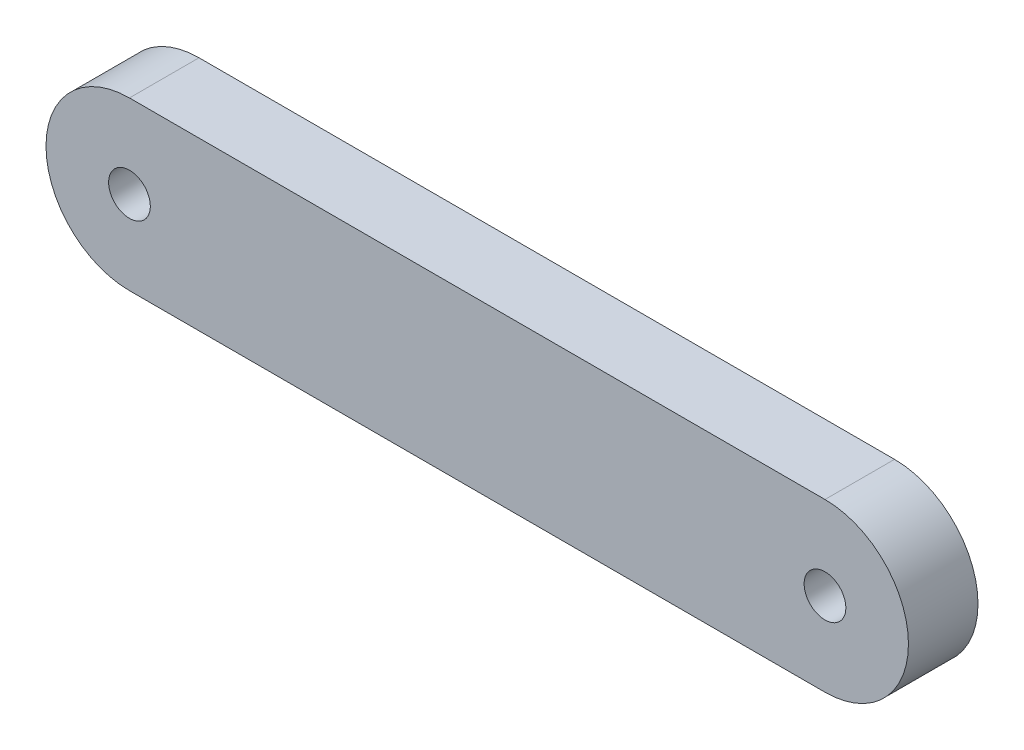
SolidWorks part; units mm, degrees
ref_plane "Plan de face" through (0, 0, 0) normal (0, 0, 1) x (1, 0, 0)
ref_plane "Plan de dessus" through (0, 0, 0) normal (0, 1, 0) x (1, 0, 0)
ref_plane "Plan de droite" through (0, 0, 0) normal (1, 0, 0) x (0, 0, -1)
sketch "Esquisse1" plane through (0, 0, 0) normal (0, 0, 1) x (1, 0, 0)
  line L0 (-25, 0) -> (25, 0) construction
  line L1 (-25, 6) -> (25, 6)
  line L2 (-25, -6) -> (25, -6)
  arc A0 (-25, 6) -> (-25, -6) centre (-25, 0) ccw
  arc A1 (25, -6) -> (25, 6) centre (25, 0) ccw
  circle A2 centre (-25, 0) radius 1.5
  circle A3 centre (25, 0) radius 1.5
  point P2 (0, 0)
  dimension "D2" = 6
  dimension "D3" = 3
  dimension "D4" = 3
  dimension "D1" = 50
extrude "Boss.-Extru.1" add sketch "Esquisse1" along normal blind 5
